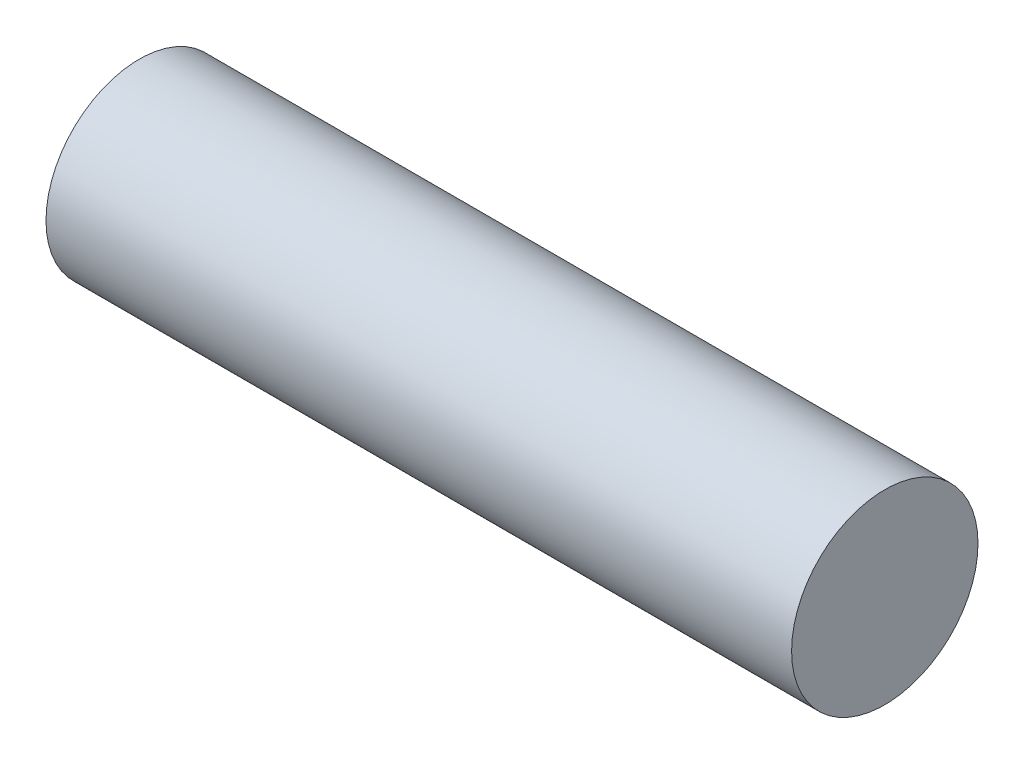
SolidWorks part; units mm, degrees
ref_plane "Front Plane" through (0, 0, 0) normal (0, 0, 1) x (1, 0, 0)
ref_plane "Top Plane" through (0, 0, 0) normal (0, 1, 0) x (1, 0, 0)
ref_plane "Right Plane" through (0, 0, 0) normal (1, 0, 0) x (0, 0, -1)
sketch "Sketch2" plane through (0, 0, 0) normal (1, 0, 0) x (0, 0, -1)
  circle A0 centre (0, 0) radius 10
extrude "Boss-Extrude1" add sketch "Sketch2" against normal blind 80
